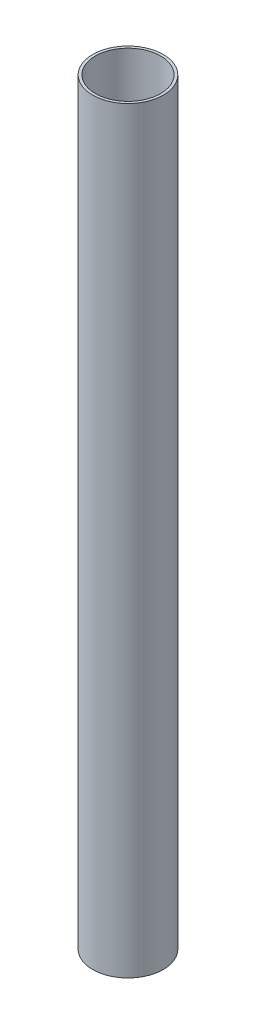
SolidWorks part; units mm, degrees
ref_plane "Front Plane" through (0, 0, 0) normal (0, 0, 1) x (1, 0, 0)
ref_plane "Top Plane" through (0, 0, 0) normal (0, 1, 0) x (1, 0, 0)
ref_plane "Right Plane" through (0, 0, 0) normal (1, 0, 0) x (0, 0, -1)
sketch "Sketch1" plane through (0, 0, 0) normal (0, 1, 0) x (1, 0, 0)
  circle A0 centre (0, 0) radius 34.29
  circle A1 centre (0, 0) radius 31.75
sketch3d "3DSketch1"
  line L0 (0, 0, 0) -> (0, 736.6, 0)
sweep "Sweep1" add profiles "Sketch1" path "3DSketch1"
